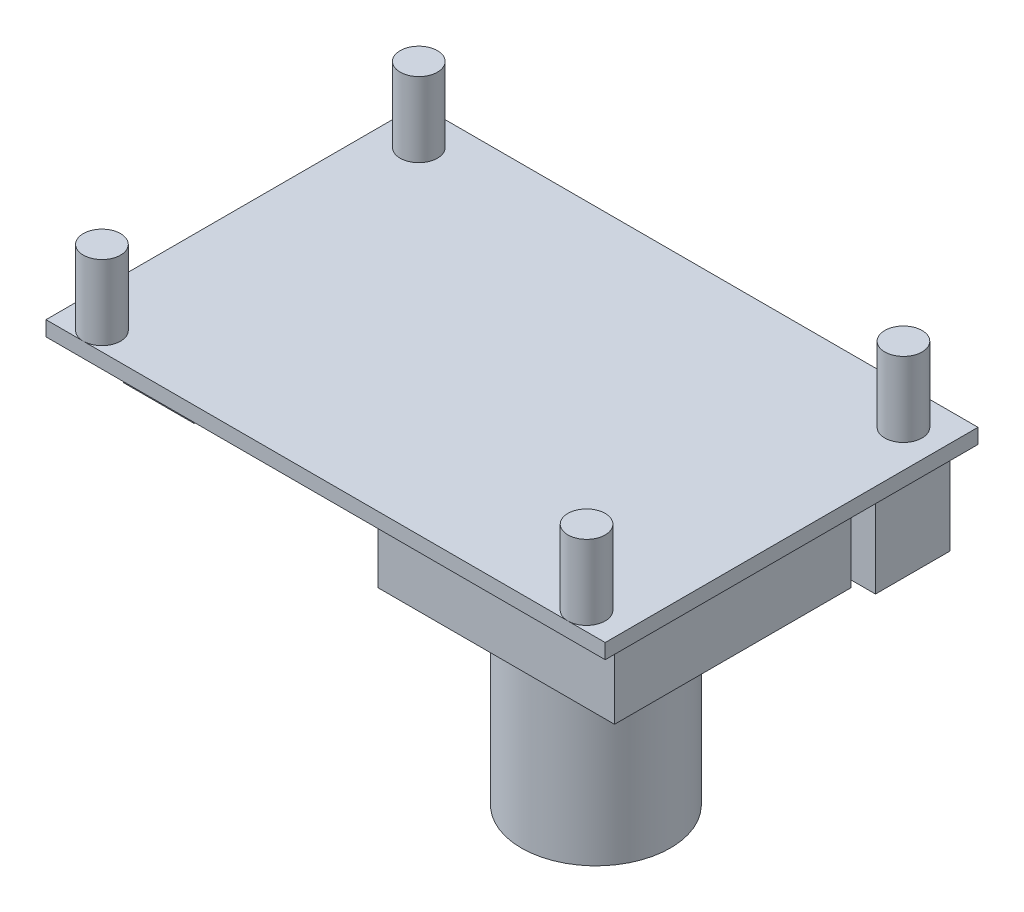
SolidWorks part; units mm, degrees
ref_plane "Front Plane" through (0, 0, 0) normal (0, 0, 1) x (1, 0, 0)
ref_plane "Top Plane" through (0, 0, 0) normal (0, 1, 0) x (1, 0, 0)
ref_plane "Right Plane" through (0, 0, 0) normal (1, 0, 0) x (0, 0, -1)
sketch "SK_P01_Standoff" plane through (0, 0, 0) normal (0, 1, 0) x (1, 0, 0)
  circle A0 centre (-26, -18) radius 2
extrude "P01_Standoff" add sketch "SK_P01_Standoff" along normal blind 8 from offset 28.6
sketch "SK_P02_Standoff" plane through (0, 0, 0) normal (0, 1, 0) x (1, 0, 0)
  circle A0 centre (-26, 16) radius 2
extrude "P02_Standoff" add sketch "SK_P02_Standoff" along normal blind 8 from offset 28.6
sketch "SK_P03_Standoff" plane through (0, 0, 0) normal (0, 1, 0) x (1, 0, 0)
  circle A0 centre (26, -18) radius 2
extrude "P03_Standoff" add sketch "SK_P03_Standoff" along normal blind 8 from offset 28.6
sketch "SK_P04_Standoff" plane through (0, 0, 0) normal (0, 1, 0) x (1, 0, 0)
  circle A0 centre (26, 16) radius 2
extrude "P04_Standoff" add sketch "SK_P04_Standoff" along normal blind 8 from offset 28.6
sketch "SK_P05_Carrierboard" plane through (0, 0, 0) normal (0, 1, 0) x (1, 0, 0)
  line L0 (-30, -20) -> (30, -20)
  line L1 (30, -20) -> (30, 20)
  line L2 (30, 20) -> (-30, 20)
  line L3 (-30, 20) -> (-30, -20)
extrude "P05_Carrierboard" add sketch "SK_P05_Carrierboard" along normal blind 1.6 from offset 27
sketch "SK_P06_INA2602compute" plane through (0, 0, 0) normal (0, 1, 0) x (1, 0, 0)
  line L0 (-28, -16) -> (-5.1, -16)
  line L1 (-5.1, -16) -> (-5.1, 7)
  line L2 (-5.1, 7) -> (-28, 7)
  line L3 (-28, 7) -> (-28, -16)
extrude "P06_INA2602compute" add sketch "SK_P06_INA2602compute" along normal blind 2.7 from offset 24.3
sketch "SK_P07_INA260terminalblock" plane through (0, 0, 0) normal (0, 1, 0) x (1, 0, 0)
  line L0 (-25, -3) -> (-15, -3)
  line L1 (-15, -3) -> (-15, 5)
  line L2 (-15, 5) -> (-25, 5)
  line L3 (-25, 5) -> (-25, -3)
extrude "P07_INA260terminalblock" add sketch "SK_P07_INA260terminalblock" along normal blind 10 from offset 14.3
sketch "SK_P08_BuckAD36V50F551V" plane through (0, 0, 0) normal (0, 1, 0) x (1, 0, 0)
  line L0 (1.6, -16) -> (27, -16)
  line L1 (27, -16) -> (27, 9.4)
  line L2 (27, 9.4) -> (1.6, 9.4)
  line L3 (1.6, 9.4) -> (1.6, -16)
extrude "P08_BuckAD36V50F551V" add sketch "SK_P08_BuckAD36V50F551V" along normal blind 9.5 from offset 17.5
sketch "SK_P09_JSTXHheadersfacedown" plane through (0, 0, 0) normal (0, 1, 0) x (1, 0, 0)
  line L0 (-28, 11) -> (28, 11)
  line L1 (28, 11) -> (28, 19)
  line L2 (28, 19) -> (-28, 19)
  line L3 (-28, 19) -> (-28, 11)
extrude "P09_JSTXHheadersfacedown" add sketch "SK_P09_JSTXHheadersfacedown" along normal blind 10.4 from offset 16.6
sketch "SK_P10_D2idealdiode" plane through (0, 0, 0) normal (0, 1, 0) x (1, 0, 0)
  line L0 (-24, -17.7) -> (-16.4, -17.7)
  line L1 (-16.4, -17.7) -> (-16.4, -5)
  line L2 (-16.4, -5) -> (-24, -5)
  line L3 (-24, -5) -> (-24, -17.7)
extrude "P10_D2idealdiode" add sketch "SK_P10_D2idealdiode" along normal blind 2.4 from offset 24.6
sketch "SK_P11_C14700uF25V" plane through (0, 0, 0) normal (0, 1, 0) x (1, 0, 0)
  circle A0 centre (16, -7) radius 8
extrude "P11_C14700uF25V" add sketch "SK_P11_C14700uF25V" along normal blind 27
